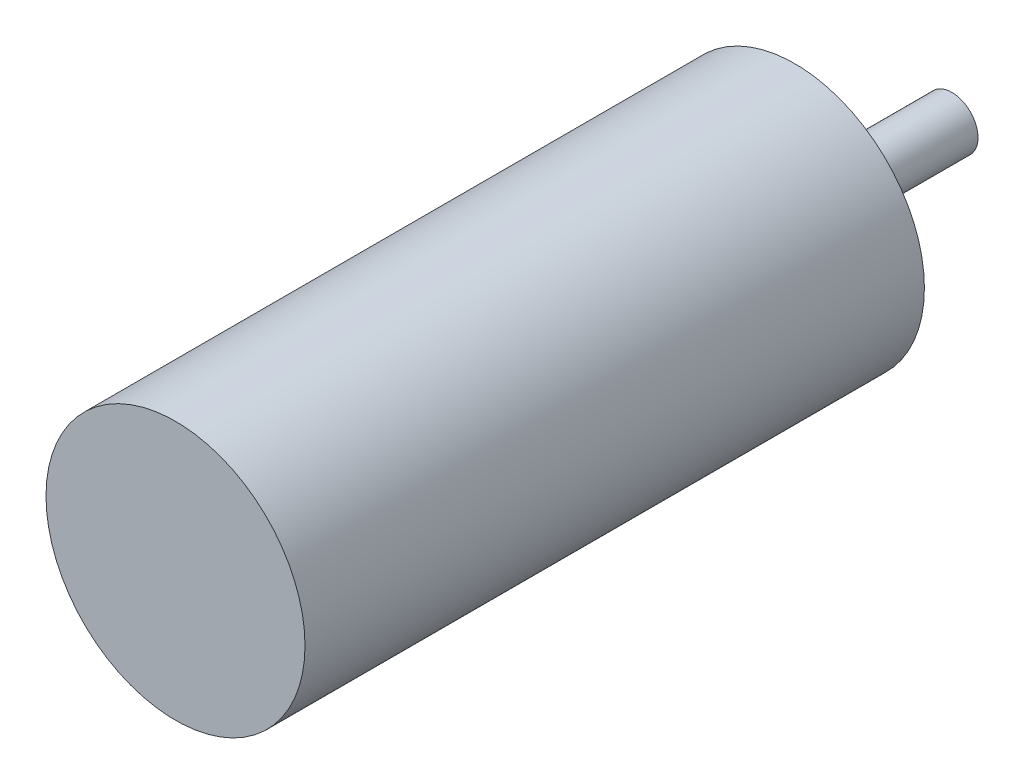
SolidWorks part; units mm, degrees
ref_plane "Front Plane" through (0, 0, 0) normal (0, 0, 1) x (1, 0, 0)
ref_plane "Top Plane" through (0, 0, 0) normal (0, 1, 0) x (1, 0, 0)
ref_plane "Right Plane" through (0, 0, 0) normal (1, 0, 0) x (0, 0, -1)
sketch "Sketch2" plane through (0, 0, 0) normal (0, 0, 1) x (1, 0, 0)
  circle A0 centre (0, 0) radius 19.8
  dimension "D1" = 39.6
extrude "Boss-Extrude1" add sketch "Sketch2" against normal blind 94.7
sketch "Sketch3" plane through (0, 0, -94.7) normal (0, 0, -1) x (-1, 0, 0)
  circle A0 centre (0, 0) radius 4
  dimension "D1" = 8
extrude "Boss-Extrude2" add sketch "Sketch3" along normal blind 24
